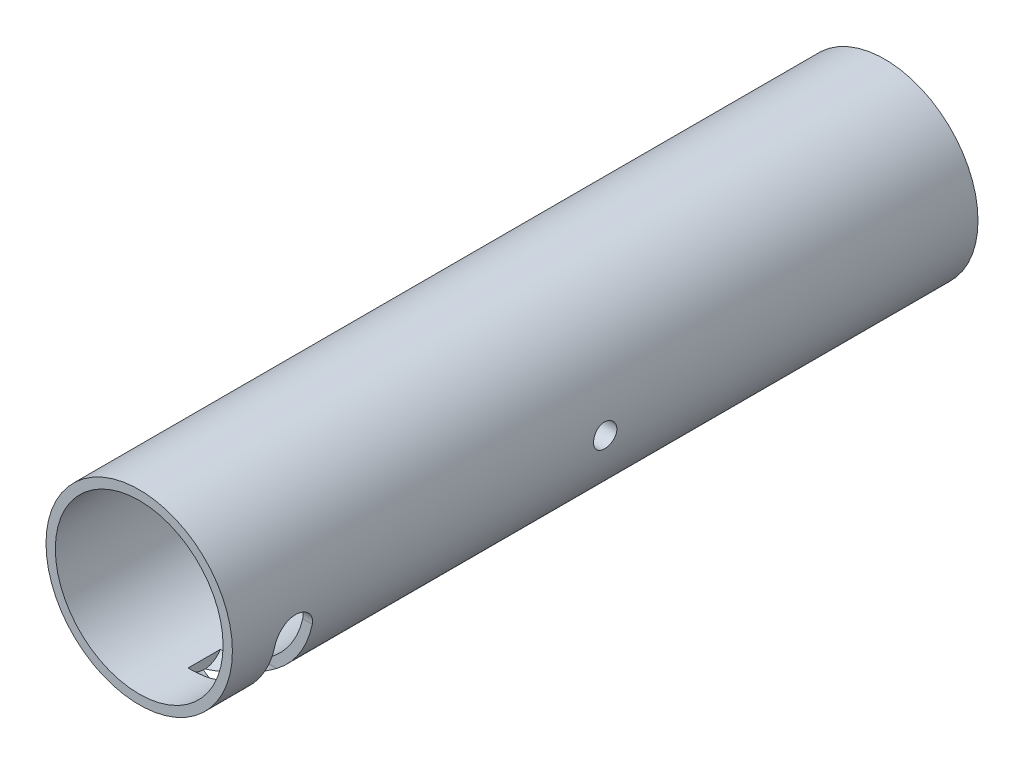
SolidWorks part; units mm, degrees
material "PE haute densité"
ref_plane "Plan de face" through (0, 0, 0) normal (0, 0, 1) x (1, 0, 0)
ref_plane "Plan de dessus" through (0, 0, 0) normal (0, 1, 0) x (1, 0, 0)
ref_plane "Plan de droite" through (0, 0, 0) normal (1, 0, 0) x (0, 0, -1)
sketch "Esquisse2" plane through (0, 0, 0) normal (0, 0, 1) x (1, 0, 0)
  circle A0 centre (0, 0) radius 50
  dimension "D1" = 100
extrude "Boss.-Extru.1" add sketch "Esquisse2" along normal mid plane 400
sketch "Esquisse3" plane through (0, 0, 0) normal (1, 0, 0) x (0, 0, -1)
  circle A0 centre (0, 0) radius 6.25
  dimension "D1" = 12.5
extrude "Enlèv. mat.-Extru.1" cut sketch "Esquisse3" against normal through all both and the other way through all
sketch "Esquisse4" plane through (0, 0, 200) normal (0, 0, 1) x (1, 0, 0)
  circle A0 centre (0, 0) radius 45
  dimension "D1" = 90
extrude "Enlèv. mat.-Extru.2" cut sketch "Esquisse4" against normal blind 100 and the other way through all
mirror "Symétrie1" about plane through (0, 0, 0) normal (0, 0, 1) of "Enlèv. mat.-Extru.2"
ref_plane "Plan1" through (50, 0, 0) normal (1, 0, 0) x (0, 0, -1)
sketch "Esquisse5" plane through (50, 0, 0) normal (1, 0, 0) x (0, 0, -1)
  line L0 (0, 0) -> (-196.4675, 0) construction
  line L1 (-166.1403, 0) -> (-166.1403, -50) construction
  line L2 (-200, -50) -> (200, -50) construction
  line L3 (-166.1403, -10) -> (-166.1403, -40) construction
  line L4 (-156.1403, -10) -> (-156.1403, -40)
  line L5 (-176.1403, -10) -> (-176.1403, -40)
  arc A0 (-156.1403, -10) -> (-176.1403, -10) centre (-166.1403, -10) ccw
  arc A1 (-176.1403, -40) -> (-156.1403, -40) centre (-166.1403, -40) ccw
  point P9 (-166.1403, -25)
  point P14 (-166.1403, 0)
  dimension "D1" = 10
extrude "Enlèv. mat.-Extru.11" cut sketch "Esquisse5" against normal blind 49 and the other way through all
